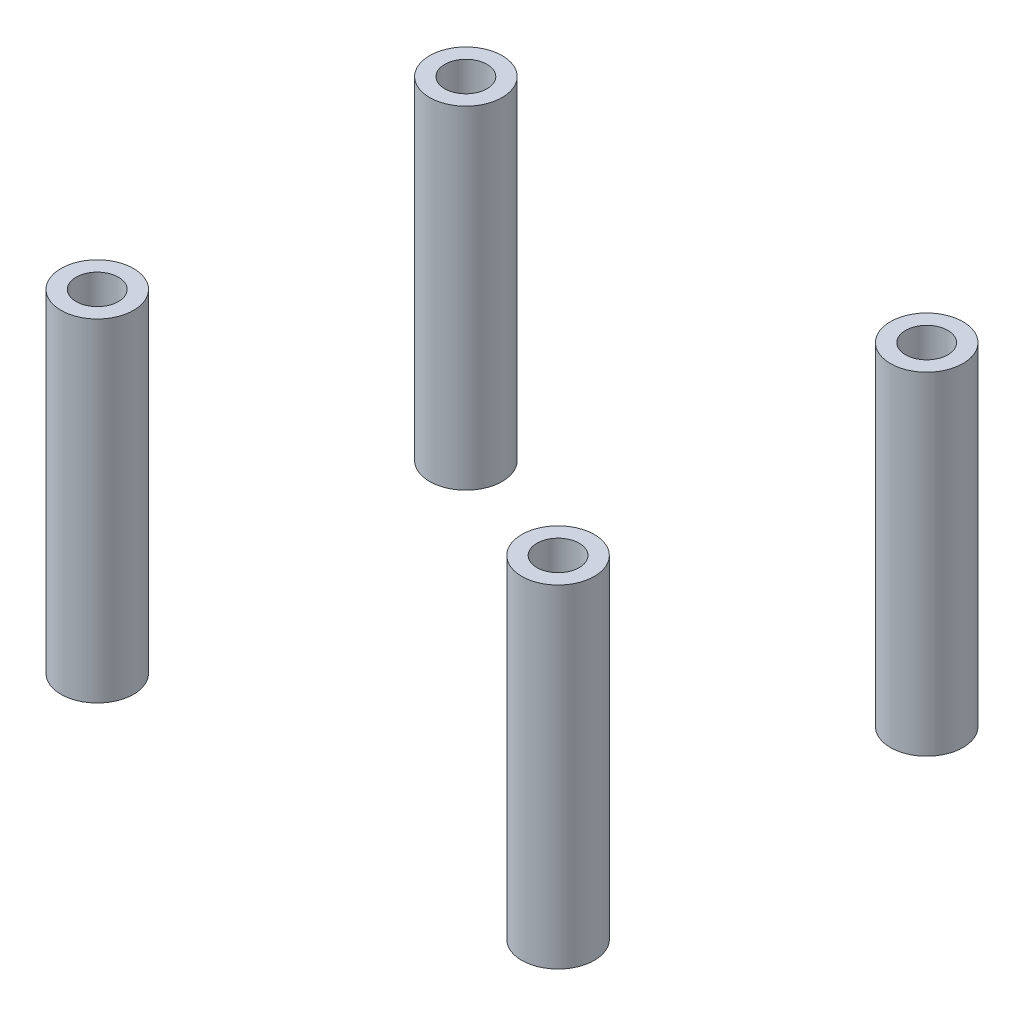
SolidWorks part; units mm, degrees
ref_plane "Front Plane" through (0, 0, 0) normal (0, 0, 1) x (1, 0, 0)
ref_plane "Top Plane" through (0, 0, 0) normal (0, 1, 0) x (1, 0, 0)
ref_plane "Right Plane" through (0, 0, 0) normal (1, 0, 0) x (0, 0, -1)
sketch "Sketch1" plane through (0, 0, 0) normal (0, 1, 0) x (1, 0, 0)
  line L1 (-19.05, -15.24) -> (19.05, -15.24) construction
  line L2 (-19.05, -15.24) -> (-19.05, 15.24) construction
  line L3 (-19.05, 15.24) -> (19.05, 15.24) construction
  line L4 (19.05, -15.24) -> (19.05, 15.24) construction
  line L5 (-19.05, -15.24) -> (19.05, 15.24) construction
  line L6 (-19.05, 15.24) -> (19.05, -15.24) construction
  circle A0 centre (-19.05, 15.24) radius 3
  circle A1 centre (19.05, 15.24) radius 3
  circle A2 centre (19.05, -15.24) radius 3
  circle A3 centre (-19.05, -15.24) radius 3
  circle A4 centre (-19.05, -15.24) radius 1.75
  circle A5 centre (19.05, -15.24) radius 1.75
  circle A6 centre (19.05, 15.24) radius 1.75
  circle A7 centre (-19.05, 15.24) radius 1.75
  point P0 (0, 0)
  dimension "D1" = 30.48
  dimension "D3" = 3.5
  dimension "D4" = 6
  dimension "D2" = 38.1
extrude "Boss-Extrude1" add sketch "Sketch1" along normal blind 27.5
